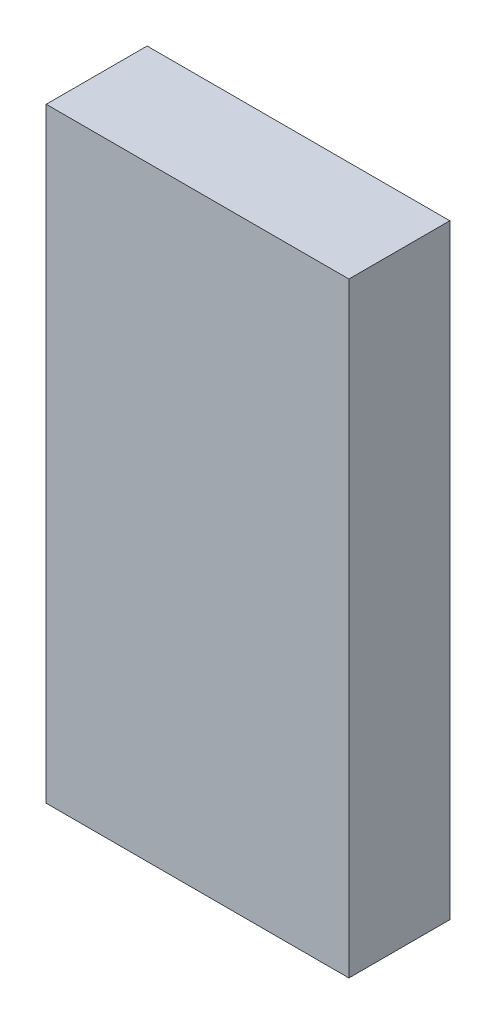
SolidWorks part; units mm, degrees
ref_plane "Front Plane" through (0, 0, 0) normal (0, 0, 1) x (1, 0, 0)
ref_plane "Top Plane" through (0, 0, 0) normal (0, 1, 0) x (1, 0, 0)
ref_plane "Right Plane" through (0, 0, 0) normal (1, 0, 0) x (0, 0, -1)
sketch "Sketch1" plane through (0, 0, 0) normal (0, 0, 1) x (1, 0, 0)
  line L0 (-38.1, 0) -> (-38.1, -76.2)
  line L5 (0, 0) -> (-38.1, 0)
  line L6 (0, 0) -> (0, -76.2)
  line L7 (0, -76.2) -> (-38.1, -76.2)
  point P2 (-50.8, -0.3556)
  dimension "D1" = 38.1
  dimension "D2" = 76.2
extrude "Boss-Extrude1" add sketch "Sketch1" against normal blind 12.7
